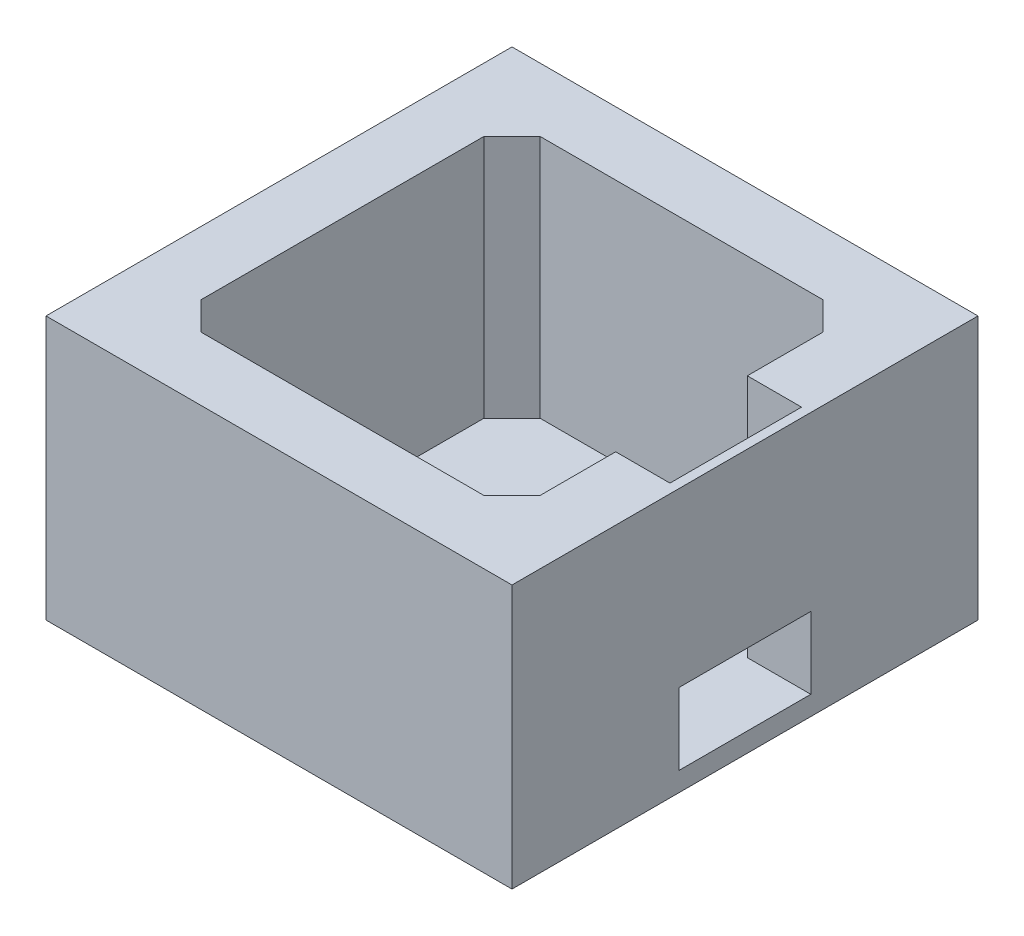
SolidWorks part; units mm, degrees
ref_plane "Front Plane" through (0, 0, 0) normal (0, 0, 1) x (1, 0, 0)
ref_plane "Top Plane" through (0, 0, 0) normal (0, 1, 0) x (1, 0, 0)
ref_plane "Right Plane" through (0, 0, 0) normal (1, 0, 0) x (0, 0, -1)
sketch "Sketch1" plane through (0, 0, 0) normal (0, 1, 0) x (1, 0, 0)
  line L1 (0, 0) -> (58.42, 0)
  line L2 (0, 0) -> (0, 58.42)
  line L3 (0, 58.42) -> (58.42, 58.42)
  line L4 (58.42, 0) -> (58.42, 58.42)
  dimension "D1" = 58.42
  dimension "D2" = 58.42
extrude "Boss-Extrude1" add sketch "Sketch1" along normal blind 33.02
sketch "Sketch2" plane through (0, 33.02, 0) normal (0, 1, 0) x (1, 0, 0)
  line L0 (11.4955, 50.46) -> (46.9245, 50.46)
  line L1 (46.9245, 50.46) -> (50.46, 46.9245)
  line L2 (50.46, 46.9245) -> (50.46, 37.46)
  line L3 (50.46, 11.4955) -> (46.9245, 7.96)
  line L4 (46.9245, 7.96) -> (11.4955, 7.96)
  line L5 (11.4955, 7.96) -> (7.96, 11.4955)
  line L6 (7.96, 11.4955) -> (7.96, 46.9245)
  line L7 (7.96, 46.9245) -> (11.4955, 50.46)
  line L8 (50.46, 20.96) -> (50.46, 11.4955)
  line L9 (50.46, 37.46) -> (57.26, 37.46)
  line L10 (50.46, 20.96) -> (57.26, 20.96)
  line L11 (57.26, 37.46) -> (57.26, 20.96)
  line L12 (58.42, 58.42) -> (0, 58.42) construction
  line L13 (0, 58.42) -> (0, 0) construction
  point P8 (29.21, 7.96)
  point P9 (7.96, 29.21)
  point P14 (57.26, 29.21)
  point P17 (29.21, 58.42)
  point P18 (29.21, 50.46)
  point P21 (0, 29.21)
  dimension "D1" = 5
  dimension "D2" = 42.5
  dimension "D3" = 135
  dimension "D4" = 135
  dimension "D5" = 135
  dimension "D6" = 42.5
  dimension "D7" = 16.5
  dimension "D8" = 6.8
extrude "Cut-Extrude1" cut sketch "Sketch2" against normal blind 30.6
sketch "Sketch3" plane through (58.42, 0, 0) normal (1, 0, 0) x (0, 0, -1)
  line L0 (20.96, 11.42) -> (37.46, 11.42)
  line L1 (20.96, 11.42) -> (20.96, 2.42)
  line L2 (20.96, 2.42) -> (37.46, 2.42)
  line L3 (37.46, 11.42) -> (37.46, 2.42)
  line L4 (0, 33.02) -> (58.42, 33.02) construction
  point P4 (29.21, 33.02)
  point P7 (29.21, 11.42)
  dimension "D1" = 16.5
  dimension "D2" = 9
  dimension "D3" = 30.6
extrude "Cut-Extrude2" cut sketch "Sketch3" against normal blind 30.6
